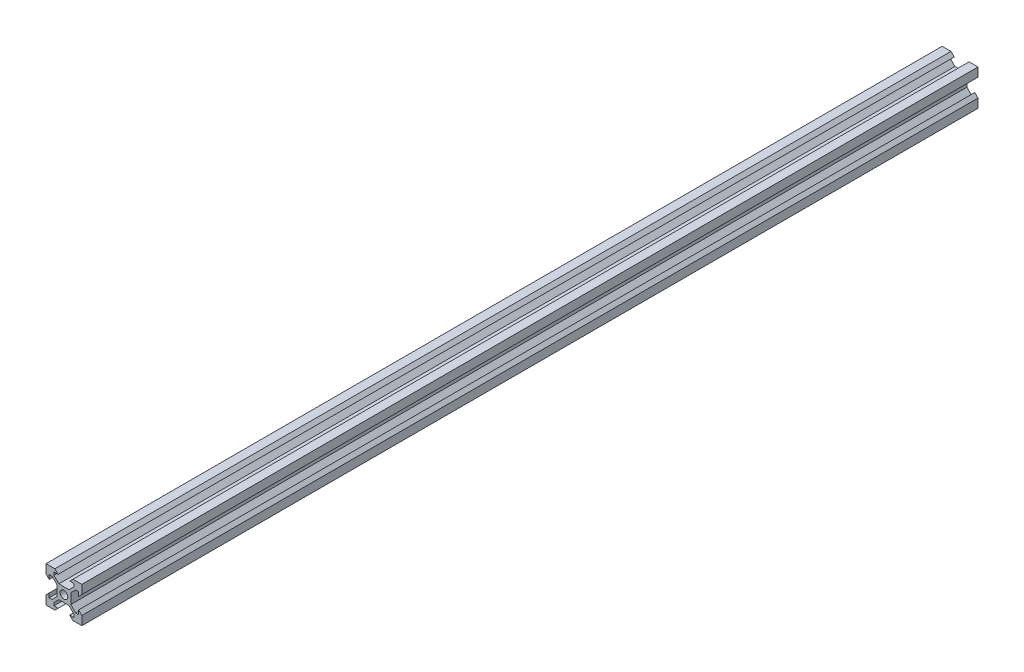
SolidWorks part; units mm, degrees
ref_plane "Alzado" through (0, 0, 0) normal (0, 0, 1) x (1, 0, 0)
ref_plane "Planta" through (0, 0, 0) normal (0, 1, 0) x (1, 0, 0)
ref_plane "Vista lateral" through (0, 0, 0) normal (1, 0, 0) x (0, 0, -1)
sketch "Croquis1" plane through (0, 0, 0) normal (0, 0, 1) x (1, 0, 0)
  line L0 (0, 0) -> (0, -20) construction
  line L2 (0, 0) -> (0, -0.5674)
  line L5 (6.175, -7.1649) -> (6.175, -12.8351)
  line L6 (7.1649, -13.825) -> (12.8351, -13.825)
  line L7 (13.825, -7.1649) -> (13.825, -12.8351)
  line L8 (7.1649, -6.175) -> (12.8351, -6.175)
  line L9 (6.175, -13.825) -> (13.825, -13.825) construction
  line L10 (13.825, -6.175) -> (13.825, -13.825) construction
  line L12 (10, -10) -> (32.1172, -10) construction
  line L13 (13.25, -18.2) -> (15.05, -20)
  line L14 (20, -20) -> (15.6, -20)
  line L15 (20, -20) -> (20, -15.6)
  line L16 (18.2, -15.6) -> (16.5899, -15.6)
  line L32 (15.6, -18.2) -> (15.6, -16.5899)
  line L33 (10, -10) -> (10, -23.2493) construction
  line L34 (4.4, -18.2) -> (4.4, -16.5899)
  line L35 (7.1649, -13.825) -> (4.4, -16.5899)
  line L36 (15.6, -18.2) -> (13.25, -18.2)
  line L38 (15.6, -20) -> (15.05, -20)
  line L40 (15.05, -20) -> (20, -20)
  line L41 (0, -20) -> (20, -20) construction
  line L42 (6.175, -12.8351) -> (3.4101, -15.6)
  line L43 (18.2, -13.25) -> (20, -15.05)
  line L44 (20, -20) -> (18.2, -20)
  line L45 (20, -20) -> (20, -15.05)
  line L48 (20, -15.05) -> (20, -20)
  line L49 (20, 0) -> (20, -20) construction
  line L50 (18.2, -15.6) -> (18.2, -13.25)
  line L51 (12.8351, -13.825) -> (15.6, -16.5899)
  line L52 (13.825, -12.8351) -> (16.5899, -15.6)
  line L53 (1.8, -15.6) -> (3.4101, -15.6)
  line L54 (1.8, -15.6) -> (1.8, -13.25)
  line L55 (1.8, -13.25) -> (0, -15.05)
  line L56 (0, 0) -> (20, 0) construction
  line L57 (0, -20) -> (0, -15.6)
  line L58 (0, -15.6) -> (0, -15.05)
  line L59 (0, -20) -> (4.4, -20)
  line L60 (0, -20) -> (4.95, -20)
  line L61 (6.75, -18.2) -> (4.95, -20)
  line L62 (4.4, -18.2) -> (6.75, -18.2)
  line L63 (1.8, -4.4) -> (3.4101, -4.4)
  line L64 (6.175, -7.1649) -> (3.4101, -4.4)
  line L65 (7.1649, -6.175) -> (4.4, -3.4101)
  line L66 (4.4, -1.8) -> (4.4, -3.4101)
  line L67 (4.4, -1.8) -> (6.75, -1.8)
  line L68 (6.75, -1.8) -> (4.95, 0)
  line L69 (0, 0) -> (4.4, 0)
  line L70 (4.4, 0) -> (4.95, 0)
  line L71 (0, 0) -> (0, -4.4)
  line L72 (0, 0) -> (0, -4.95)
  line L73 (1.8, -6.75) -> (0, -4.95)
  line L74 (1.8, -4.4) -> (1.8, -6.75)
  line L75 (15.6, -1.8) -> (15.6, -3.4101)
  line L76 (12.8351, -6.175) -> (15.6, -3.4101)
  line L77 (13.825, -7.1649) -> (16.5899, -4.4)
  line L78 (18.2, -4.4) -> (16.5899, -4.4)
  line L79 (18.2, -4.4) -> (18.2, -6.75)
  line L80 (18.2, -6.75) -> (20, -4.95)
  line L81 (20, 0) -> (20, -4.4)
  line L82 (20, -4.4) -> (20, -4.95)
  line L83 (20, 0) -> (15.6, 0)
  line L84 (20, 0) -> (15.05, 0)
  line L85 (13.25, -1.8) -> (15.05, 0)
  line L86 (15.6, -1.8) -> (13.25, -1.8)
  line L87 (6.175, -6.175) -> (13.825, -6.175) construction
  line L88 (6.175, -6.175) -> (6.175, -13.825) construction
  circle A0 centre (10, -10) radius 2.15
  point P69 (10, -10)
  dimension "D3" = 4.3
  dimension "D2" = 4
  dimension "D11" = 4.4
  dimension "D15" = 4.4
  dimension "D16" = 6.75
extrude "Saliente-Extruir2" add sketch "Croquis1" along normal blind 500 contours L86 L75 L76 L8 L65 L66 L67 L68 L70 L69 L2 L71 L72 L73 L74 L63 L64 L5 L42 L53 L54 L55 L58 L57 L59 L60 L61 L62 L34 L35 L6 L51 L32 L36 L13 L38 L40 L14 L15 L45 L43 L50 L16 L52 L7 L77 L78 L79 L80 L82 L81
